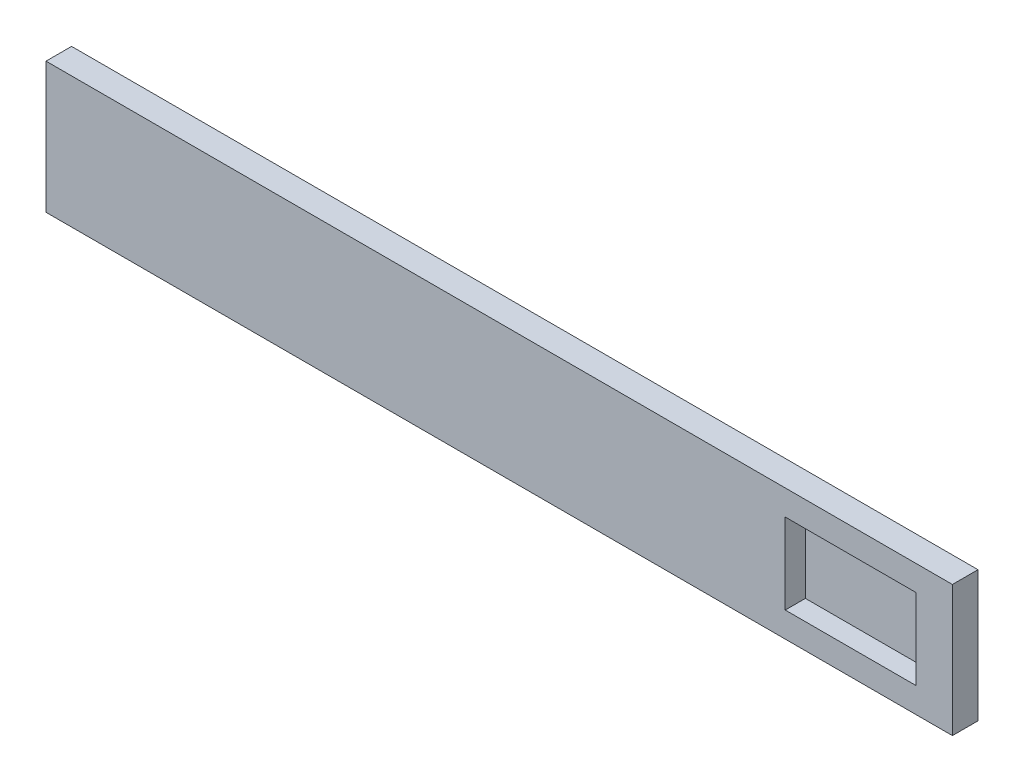
SolidWorks part; units mm, degrees
material "6063-O"
ref_plane "Front Plane" through (0, 0, 0) normal (0, 0, 1) x (1, 0, 0)
ref_plane "Top Plane" through (0, 0, 0) normal (0, 1, 0) x (1, 0, 0)
ref_plane "Right Plane" through (0, 0, 0) normal (1, 0, 0) x (0, 0, -1)
sketch "Sketch1" plane through (0, 0, 0) normal (0, 0, 1) x (1, 0, 0)
  line L1 (0, 0) -> (900, 0)
  line L2 (0, 0) -> (0, 130)
  line L3 (0, 130) -> (900, 130)
  line L4 (900, 0) -> (900, 130)
  dimension "D1" = 900
  dimension "D2" = 130
extrude "Boss-Extrude1" add sketch "Sketch1" along normal blind 25.4
sketch "Sketch3" plane through (0, 0, 25.4) normal (0, 0, 1) x (1, 0, 0)
  line L0 (900, 0) -> (900, 130) construction
  line L5 (0, 0) -> (900, 0) construction
  line L6 (450, 0) -> (450, 130) construction
  line L7 (900, 130) -> (0, 130) construction
  line L8 (734, 105) -> (734, 25)
  line L9 (864, 25) -> (734, 25)
  line L10 (864, 105) -> (864, 25)
  line L11 (864, 105) -> (734, 105)
  dimension "D1" = 25
  dimension "D2" = 36
  dimension "D3" = 80
  dimension "D4" = 130
extrude "Cut-Extrude3" cut sketch "Sketch3" against normal blind 20
